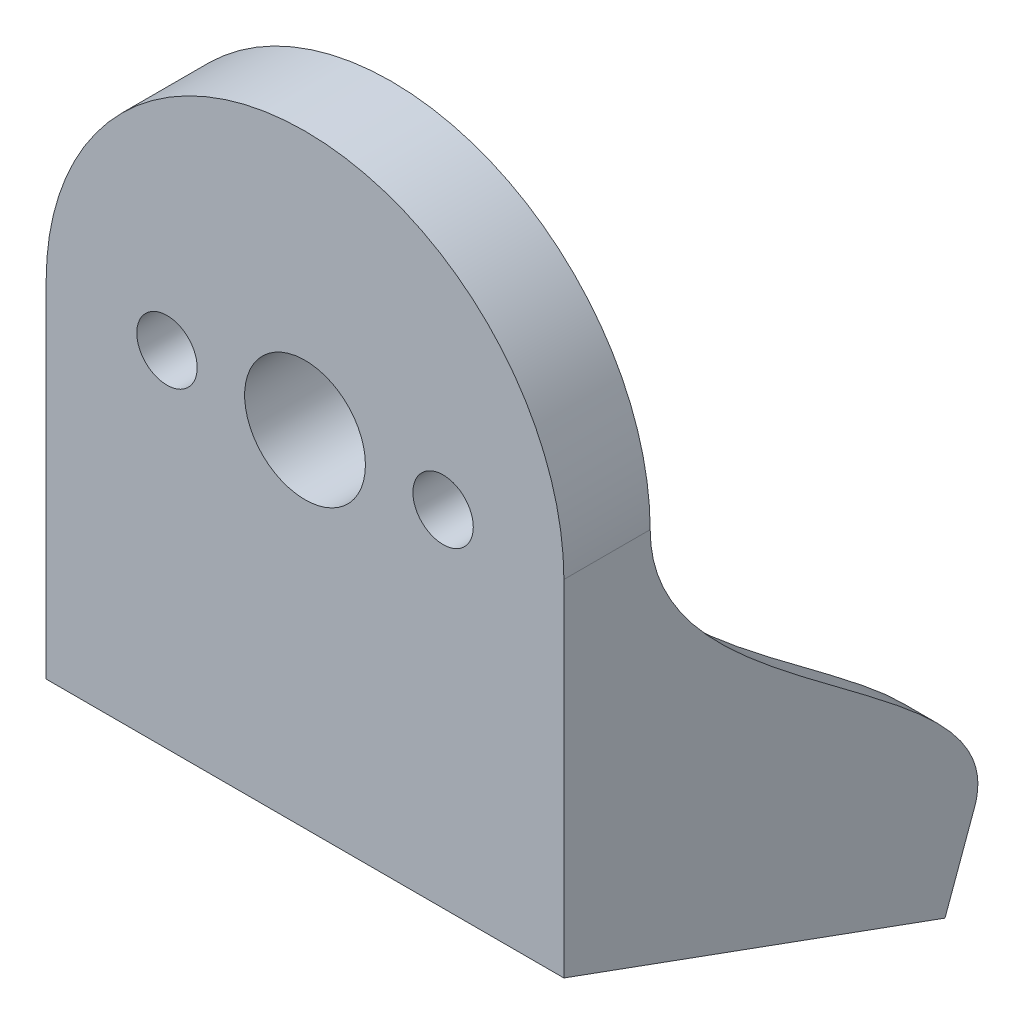
SolidWorks part; units mm, degrees
ref_plane "Plan de face" through (0, 0, 0) normal (0, 0, 1) x (1, 0, 0)
ref_plane "Plan de dessus" through (0, 0, 0) normal (0, 1, 0) x (1, 0, 0)
ref_plane "Plan de droite" through (0, 0, 0) normal (1, 0, 0) x (0, 0, -1)
sketch "Esquisse1" plane through (0, 0, 0) normal (0, 0, 1) x (1, 0, 0)
  line L1 (-15.9596, 10.3488) -> (14.0404, 10.3488) construction
  line L2 (-15.9596, 10.3488) -> (-15.9596, -9.6512)
  line L3 (-15.9596, -9.6512) -> (14.0404, -9.6512)
  line L4 (14.0404, 10.3488) -> (14.0404, -9.6512)
  arc A0 (14.0404, 10.3488) -> (-15.9596, 10.3488) centre (-0.9596, 10.3488) ccw
  circle A1 centre (-8.9596, 10.3488) radius 1.75
  circle A2 centre (7.0404, 10.3488) radius 1.75
  circle A3 centre (-0.9596, 10.3488) radius 3.5
  point P5 (-8.9596, 10.3488)
  point P6 (7.0404, 10.3488)
  dimension "D5" = 3.5
  dimension "D6" = 3.5
  dimension "D7" = 7
  dimension "D1" = 30
  dimension "D2" = 20
  dimension "D3" = 8
  dimension "D4" = 8
extrude "Boss.-Extru.1" add sketch "Esquisse1" along normal blind 5
sketch "Esquisse2" plane through (-15.9596, 0, 0) normal (-1, 0, 0) x (0, 0, 1)
  line L0 (0, -9.6512) -> (0, -6.1501)
  line L1 (0, 10.3488) -> (0, -9.6512) construction
  line L2 (0, -6.1501) -> (1.2743, -9.6512)
  line L3 (5, -9.6512) -> (0, -9.6512) construction
  line L4 (1.2743, -9.6512) -> (0, -9.6512)
  line L5 (5, -9.6512) -> (1.9464, -10.7626) construction
  dimension "D1" = 20
  dimension "D2" = 5
extrude "Enlèv. mat.-Extru.2" cut sketch "Esquisse2" against normal up to next
sketch "Esquisse4" plane through (-15.9596, 0, 0) normal (-1, 0, 0) x (0, 0, 1)
  line L0 (5, -9.6512) -> (1.7101, -10.8486)
  line L1 (1.7101, -10.8486) -> (1.2743, -9.6512)
  line L2 (1.2743, -9.6512) -> (0, -6.1501) construction
  line L3 (1.2743, -9.6512) -> (5, -9.6512)
extrude "Boss.-Extru.2" add sketch "Esquisse4" against normal up to vertex (30 mm away)
sketch "Esquisse5" plane through (0, -0.7194, -1.9766) normal (0, -0.342, -0.9397) x (-1, 0, 0)
  line L1 (15.9596, -5.7792) -> (-14.0404, -5.7792)
  line L2 (15.9596, -5.7792) -> (15.9596, -10.7792)
  line L3 (15.9596, -10.7792) -> (-14.0404, -10.7792)
  line L4 (-14.0404, -5.7792) -> (-14.0404, -10.7792)
extrude "Boss.-Extru.3" add sketch "Esquisse5" along normal blind 20
sketch "Esquisse6" plane through (-15.9596, 0, 0) normal (-1, 0, 0) x (0, 0, 1)
  line L0 (0, 10.3488) -> (0, -6.1501)
  line L1 (0, -6.1501) -> (-18.7939, -12.9905)
  line L2 (0, 25.3488) -> (0, 10.3488) construction
  line L3 (-17.0838, -17.689) -> (-18.7939, -12.9905) construction
  spline S0 degree 3 poles (0, 10.3488) (0, 0.3603) (-21.2214, -6.3208) (-18.7939, -12.9905) knots 0 0 0 0 1 1 1 1
extrude "Boss.-Extru.4" add sketch "Esquisse6" against normal blind 2
sketch "Esquisse11" plane through (14.0404, 0, 0) normal (-1, 0, 0) x (0, 0, 1)
  line L0 (0, 10.3488) -> (0, -6.1501)
  line L1 (0, -6.1501) -> (-18.7939, -12.9905)
  spline S0 degree 3 poles (0, 10.3488) (0, 0.3603) (-21.2214, -6.3208) (-18.7939, -12.9905) knots 0 0 0 0 1 1 1 1
extrude "Boss.-Extru.5" add sketch "Esquisse11" along normal blind 2
sketch "Esquisse12" plane through (0, -5.4307, 1.9766) normal (0, 0.9397, -0.342) x (1, 0, 0)
  line L0 (-13.9596, 18.1035) -> (12.0404, 18.1035) construction
  line L1 (-13.9596, 22.1035) -> (12.0404, 22.1035) construction
  line L2 (-13.9596, -3.5395) -> (-13.9596, 22.1035) construction
  line L3 (12.0404, 22.1035) -> (12.0404, -3.5395) construction
  line L5 (12.0404, 6.1035) -> (-13.9596, 6.1035) construction
  line L6 (12.0404, 22.1035) -> (12.0404, 2.1035) construction
  line L7 (-13.9596, 22.1035) -> (-13.9596, 2.1035) construction
  line L8 (12.0404, 2.1035) -> (-13.9596, 2.1035) construction
  circle A0 centre (-9.9596, 18.1035) radius 1.75
  circle A1 centre (8.0404, 18.1035) radius 1.75
  circle A2 centre (8.0404, 6.1035) radius 1.75
  circle A3 centre (-9.9596, 6.1035) radius 1.75
  point P8 (-0.9596, 18.1035)
  dimension "D2" = 3.5
  dimension "D3" = 3.5
  dimension "D7" = 3.5
  dimension "D8" = 3.5
  dimension "D1" = 4
  dimension "D4" = 4
  dimension "D5" = 4
  dimension "D6" = 4
  dimension "D9" = 4
  dimension "D10" = 4
extrude "Enlèv. mat.-Extru.3" cut sketch "Esquisse12" against normal up to next
ref_plane "Plan1" through (-0.9596, 0, 0) normal (1, 0, 0) x (0, 0, -1)
sketch "Esquisse16" plane through (-0.9596, 0, 0) normal (1, 0, 0) x (0, 0, -1)
  line L0 (18.7939, -12.9905) -> (0, -6.1501)
  line L1 (0, -6.1501) -> (0, 10.3488) construction
  line L2 (0, -6.1501) -> (0, -2.5346)
  line L3 (0, -2.5346) -> (18.7939, -12.9905)
extrude "Boss.-Extru.6" add sketch "Esquisse16" along normal blind 4 and the other way blind 4
